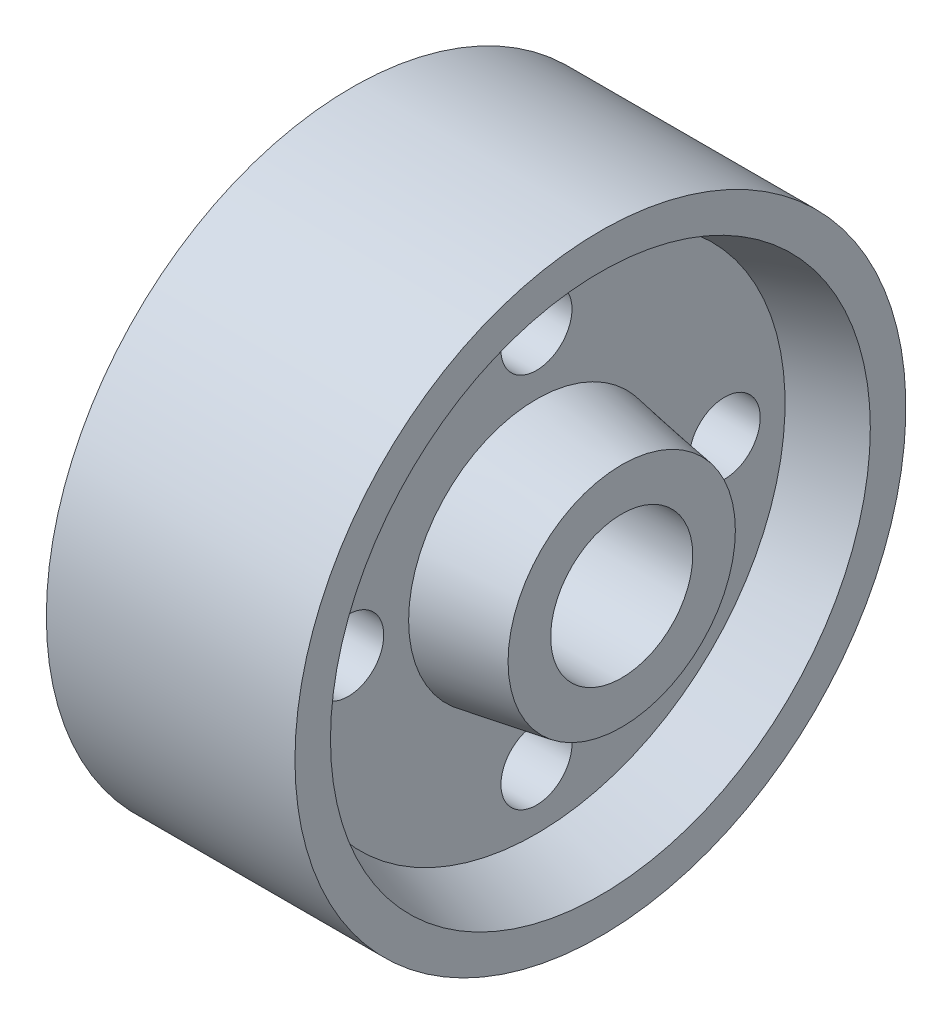
SolidWorks part; units mm, degrees
ref_plane "Front Plane" through (0, 0, 0) normal (0, 0, 1) x (1, 0, 0)
ref_plane "Top Plane" through (0, 0, 0) normal (0, 1, 0) x (1, 0, 0)
ref_plane "Right Plane" through (0, 0, 0) normal (1, 0, 0) x (0, 0, -1)
sketch "Sketch3" plane through (0, 0, 0) normal (0, 1, 0) x (1, 0, 0)
  line L0 (0, 0) -> (52.7569, 0) construction
  line L1 (0, 0) -> (0, 16)
  line L2 (0, 16) -> (12, 18)
  line L3 (12, 18) -> (12, 35)
  line L4 (12, 35) -> (3, 38)
  line L5 (3, 38) -> (3, 43)
  line L6 (3, 43) -> (38, 43)
  line L7 (20.5, 43) -> (20.5, 0) construction
  line L8 (41, 0) -> (41, 16)
  line L9 (41, 16) -> (29, 18)
  line L10 (29, 18) -> (29, 35)
  line L11 (29, 35) -> (38, 38)
  line L12 (38, 38) -> (38, 43)
  line L13 (0, 0) -> (41, 0)
  dimension "D1" = 32
  dimension "D2" = 36
  dimension "D3" = 70
  dimension "D4" = 76
  dimension "D5" = 86
  dimension "D6" = 12
  dimension "D7" = 17.5
  dimension "D8" = 20.5
revolve "Revolve1" add sketch "Sketch3" angle 360 about L0
sketch "Sketch4" plane through (41, 0, 0) normal (1, 0, 0) x (0, 0, -1)
  line L0 (0, 0) -> (-26.5, 0) construction
  line L2 (0, 0) -> (0, -26.5) construction
  circle A0 centre (0, 0) radius 26.5 construction
  circle A1 centre (0, 26.5) radius 5
  circle A2 centre (26.5, 0) radius 5
  circle A3 centre (0, -26.5) radius 5
  circle A4 centre (-26.5, 0) radius 5
  point P8 (0, 0)
  point P17 (0, 0)
  dimension "D1" = 53
  dimension "D2" = 10
  dimension "D3" = 4
extrude "Cut-Extrude1" cut sketch "Sketch4" against normal through all
sketch "Sketch5" plane through (41, 0, 0) normal (1, 0, 0) x (0, 0, -1)
  circle A0 centre (0, 0) radius 10
  dimension "D1" = 20
extrude "Cut-Extrude2" cut sketch "Sketch5" against normal through all
